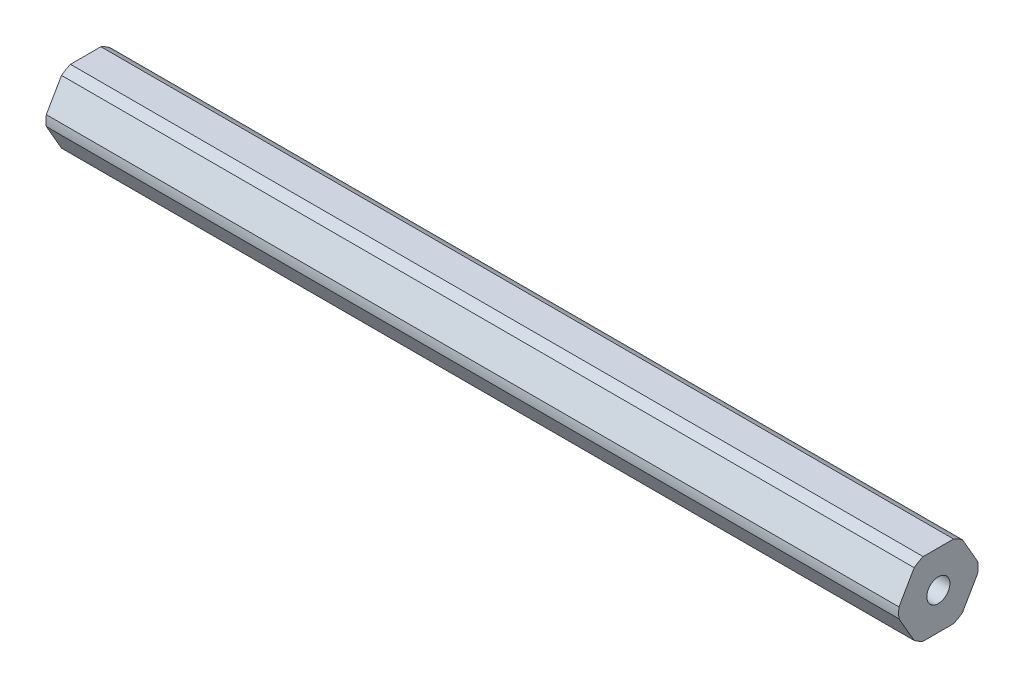
SolidWorks part; units mm, degrees
material "6061-T6 (SS)"
ref_plane "Front Plane" through (0, 0, 0) normal (0, 0, 1) x (1, 0, 0)
ref_plane "Top Plane" through (0, 0, 0) normal (0, 1, 0) x (1, 0, 0)
ref_plane "Right Plane" through (0, 0, 0) normal (1, 0, 0) x (0, 0, -1)
sketch "Sketch1" plane through (0, 0, 0) normal (1, 0, 0) x (0, 0, -1)
  line L1 (7.3323, 0) -> (3.6662, 6.35)
  line L2 (3.6662, 6.35) -> (-3.6662, 6.35)
  line L3 (-3.6662, 6.35) -> (-7.3323, 0)
  line L4 (-7.3323, 0) -> (-3.6662, -6.35)
  line L5 (-3.6662, -6.35) -> (3.6662, -6.35)
  line L6 (3.6662, -6.35) -> (7.3323, 0)
  circle A0 centre (0, 0) radius 6.35 construction
  circle A1 centre (0, 0) radius 6.875
  circle A2 centre (0, 0) radius 2
  dimension "D1" = 12.7
  dimension "D2" = 13.75
  dimension "D3" = 4
extrude "Boss-Extrude1" add sketch "Sketch1" along normal mid plane 147.6375 contours L1 A1 L2 L3 L4 L5 L6 A2
equation "\"D2@Sketch1\"=13.75MM"
equation "\"D3@Sketch1\"=4mm"
